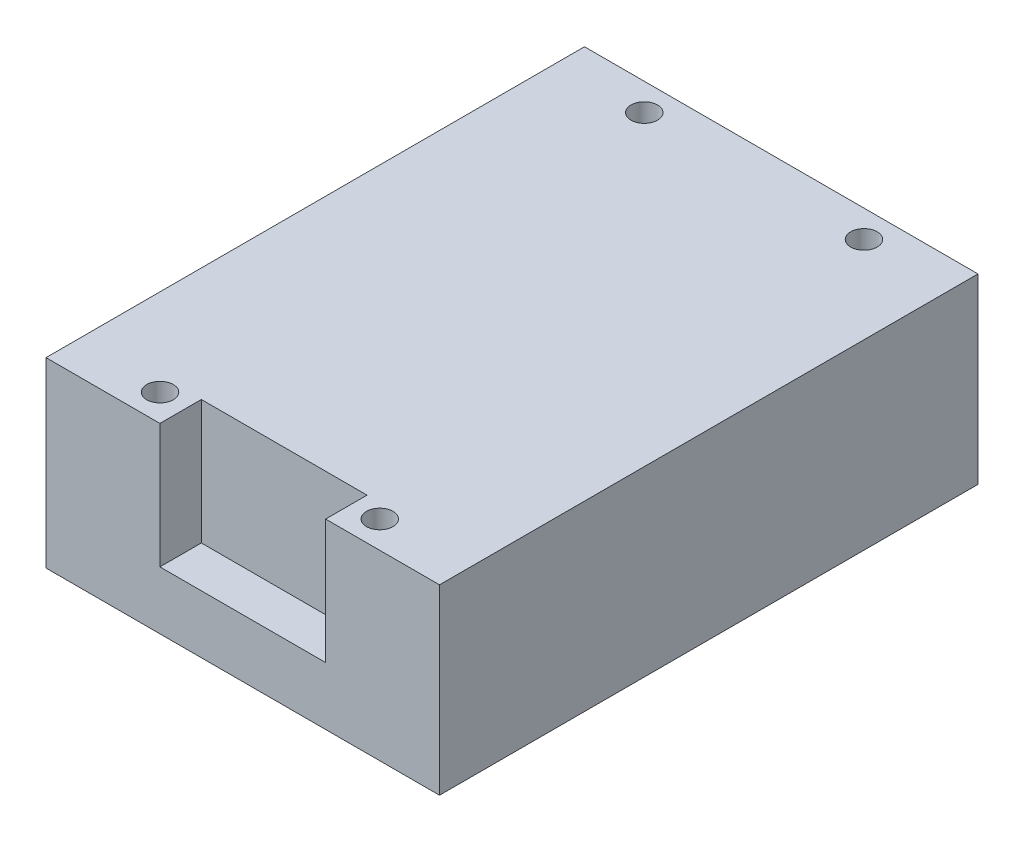
SolidWorks part; units mm, degrees
ref_plane "Front Plane" through (0, 0, 0) normal (0, 0, 1) x (1, 0, 0)
ref_plane "Top Plane" through (0, 0, 0) normal (0, 1, 0) x (1, 0, 0)
ref_plane "Right Plane" through (0, 0, 0) normal (1, 0, 0) x (0, 0, -1)
sketch "Sketch1" plane through (0, 0, 0) normal (0, 1, 0) x (1, 0, 0)
  line L1 (-23.75, 32.5) -> (23.75, 32.5)
  line L2 (-23.75, 32.5) -> (-23.75, -32.5)
  line L3 (-23.75, -32.5) -> (23.75, -32.5)
  line L4 (23.75, 32.5) -> (23.75, -32.5)
  line L5 (-23.75, 32.5) -> (23.75, -32.5) construction
  line L6 (-23.75, -32.5) -> (23.75, 32.5) construction
  point P0 (0, 0)
  dimension "D1" = 65
  dimension "D2" = 47.5
extrude "Boss-Extrude1" add sketch "Sketch1" along normal blind 22
sketch "Sketch2" plane through (0, 22, 0) normal (0, 1, 0) x (1, 0, 0)
  line L1 (-13.26, 29.225) -> (13.26, 29.225) construction
  line L2 (-13.26, 29.225) -> (-13.26, -29.225) construction
  line L3 (-13.26, -29.225) -> (13.26, -29.225) construction
  line L4 (13.26, 29.225) -> (13.26, -29.225) construction
  line L5 (-13.26, 29.225) -> (13.26, -29.225) construction
  line L6 (-13.26, -29.225) -> (13.26, 29.225) construction
  circle A0 centre (-13.26, 29.225) radius 1.6
  circle A1 centre (13.26, 29.225) radius 1.6
  circle A2 centre (13.26, -29.225) radius 1.6
  circle A3 centre (-13.26, -29.225) radius 1.6
  point P0 (0, 0)
  dimension "D1" = 3.2
  dimension "D2" = 26.52
  dimension "D3" = 58.45
extrude "Cut-Extrude1" cut sketch "Sketch2" against normal through all
sketch "Sketch4" plane through (0, 22, 0) normal (0, 1, 0) x (1, 0, 0)
  line L0 (-23.75, -32.5) -> (23.75, -32.5) construction
  line L1 (-10, -32.5) -> (10, -32.5)
  line L2 (-10, -32.5) -> (-10, -27.5)
  line L3 (-10, -27.5) -> (10, -27.5)
  line L4 (10, -32.5) -> (10, -27.5)
  line L5 (0, -27.5) -> (0, 0) construction
  dimension "D1" = 20
  dimension "D2" = 5
extrude "Cut-Extrude2" cut sketch "Sketch4" against normal blind 15
